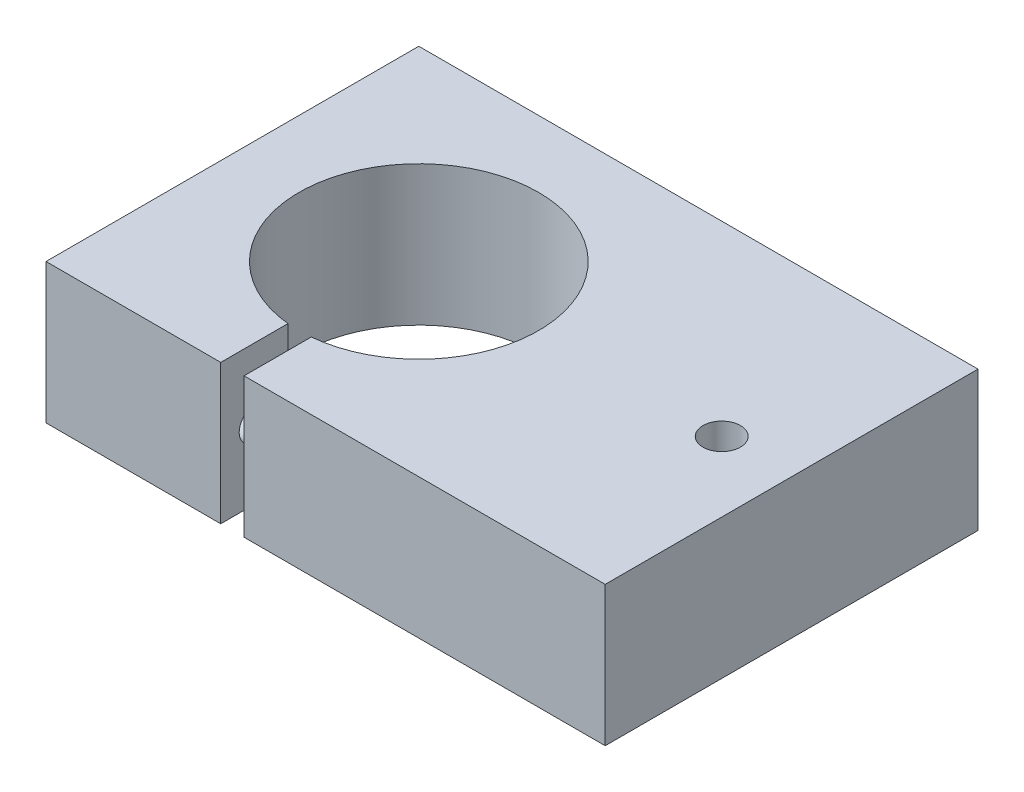
SolidWorks part; units mm, degrees
ref_plane "Front Plane" through (0, 0, 0) normal (0, 0, 1) x (1, 0, 0)
ref_plane "Top Plane" through (0, 0, 0) normal (0, 1, 0) x (1, 0, 0)
ref_plane "Right Plane" through (0, 0, 0) normal (1, 0, 0) x (0, 0, -1)
sketch "Sketch1" plane through (0, 0, 0) normal (0, 1, 0) x (1, 0, 0)
  line L1 (-38.1, -25.4) -> (38.1, -25.4)
  line L2 (-38.1, -25.4) -> (-38.1, 25.4)
  line L3 (-38.1, 25.4) -> (38.1, 25.4)
  line L4 (38.1, -25.4) -> (38.1, 25.4)
  line L5 (-38.1, -25.4) -> (38.1, 25.4) construction
  line L6 (-38.1, 25.4) -> (38.1, -25.4) construction
  point P0 (0, 0)
  dimension "D1" = 76.2
  dimension "D2" = 50.8
extrude "Boss-Extrude1" add sketch "Sketch1" along normal mid plane 19.05 contours L1 L4 L3 L2
sketch "Sketch2" plane through (0, 9.525, 0) normal (0, 1, 0) x (1, 0, 0)
  line L0 (-10.4775, 0) -> (10.4775, 0) construction
  line L2 (-38.1, -25.4) -> (-38.1, 25.4) construction
  circle A0 centre (-12.7, 0) radius 16.3195
  dimension "D1" = 32.639
  dimension "D2" = 25.4
extrude "Cut-Extrude1" cut sketch "Sketch2" against normal through all
sketch "Sketch3" plane through (0, 9.525, 0) normal (0, 1, 0) x (1, 0, 0)
  line L1 (-11.1125, -28.0194) -> (-14.2875, -28.0194)
  line L2 (-11.1125, -28.0194) -> (-11.1125, 0)
  line L3 (-11.1125, 0) -> (-14.2875, 0)
  line L4 (-14.2875, -28.0194) -> (-14.2875, 0)
  line L5 (-11.1125, -28.0194) -> (-14.2875, 0) construction
  line L6 (-11.1125, 0) -> (-14.2875, -28.0194) construction
  point P0 (-12.7, -14.0097)
  point P6 (-12.7, 0)
  point P7 (-12.7, 0)
  dimension "D1" = 3.175
extrude "Cut-Extrude2" cut sketch "Sketch3" against normal through all
sketch "Sketch4" plane through (-38.1, 0, 0) normal (-1, 0, 0) x (0, 0, 1)
  line L0 (27.94, 0) -> (-27.94, 0) construction
  line L1 (25.4, 9.525) -> (25.4, -9.525) construction
  point P0 (20.6375, 0)
  dimension "D1" = 4.7625
hole_wizard "CBORE for #8 Socket Head Cap Screw1" positions "Sketch5" profile "Sketch7" counterbore size "#8" standard "ANSI Inch"
sketch "Sketch5" plane through (-38.1, 0, 0) normal (-1, 0, 0) x (0, 0, 1)
  point P0 (20.6375, 0)
sketch "Sketch7" plane through (-38.1, 0, 20.6375) normal (0, 1, 0) x (0, 0, 1)
  line L0 (0, 0) -> (0, 23.8125)
  line L1 (0, 23.8125) -> (2.2479, 23.8125)
  line L3 (2.2479, 23.8125) -> (2.2479, 4.1656)
  line L4 (2.2479, 4.1656) -> (3.9687, 4.1656)
  line L5 (3.9687, 4.1656) -> (3.9687, 0)
  line L7 (3.9687, 0) -> (0, 0)
  line L11 (0, -6.35) -> (0, 107.95) construction
  dimension "Thru Hole Dia." = 4.4958
  dimension "Thru Hole Depth" = 23.8125
  dimension "C'Bore Dia." = 7.9375
  dimension "C'Bore Depth" = 4.1656
hole_wizard "#8-32 Tapped Hole1" positions "Sketch8" profile "Sketch10" tap size "#8-32" standard "ANSI Inch"
sketch "Sketch8" plane through (-11.1125, 0, 0) normal (-1, 0, 0) x (0, 0, 1)
  point P0 (20.6375, 0)
cosmetic thread "Hole Thread1" parameters "D1"=36.576, "D2"=4.1656
sketch "Sketch10" plane through (-11.1125, 0, 20.6375) normal (0, 1, 0) x (0, 0, 1)
  line L0 (0, 0) -> (0, 13.7378)
  line L1 (0, 13.7378) -> (1.7272, 12.7)
  line L2 (1.7272, 12.7) -> (1.7272, 0)
  line L5 (1.7272, 0) -> (0, 0)
  line L10 (0, 13.7378) -> (-1.7272, 12.7) construction
  line L11 (0, -6.35) -> (0, 107.95) construction
  dimension "Tap Drill Dia." = 3.4544
  dimension "Tap Drill Depth" = 12.7
  dimension "Drill Angle" = 118
sketch "Sketch11" plane through (0, 9.525, 0) normal (0, 1, 0) x (1, 0, 0)
  line L0 (-10.4775, 0) -> (10.4775, 0) construction
  line L1 (38.1, -25.4) -> (38.1, 25.4) construction
  point P0 (28.575, 0)
  dimension "D1" = 9.525
hole_wizard "1/4-20 Tapped Hole1" positions "Sketch12" profile "Sketch13" tap size "1/4-20" standard "ANSI Inch" end condition through all
sketch "Sketch12" plane through (0, 9.525, 0) normal (0, 1, 0) x (1, 0, 0)
  point P0 (28.575, 0)
cosmetic thread "Hole Thread2" parameters "D2"=6.35
sketch "Sketch13" plane through (28.575, 9.525, 0) normal (1, 0, 0) x (0, 0, 1)
  line L0 (0, 0) -> (0, 19.05)
  line L1 (0, 19.05) -> (2.5527, 19.05)
  line L2 (2.5527, 19.05) -> (2.5527, 0)
  line L5 (2.5527, 0) -> (0, 0)
  line L11 (0, -6.35) -> (0, 107.95) construction
  dimension "Thru Tap Drill Dia." = 5.1054
  dimension "Thru Tap Drill Depth" = 19.05
